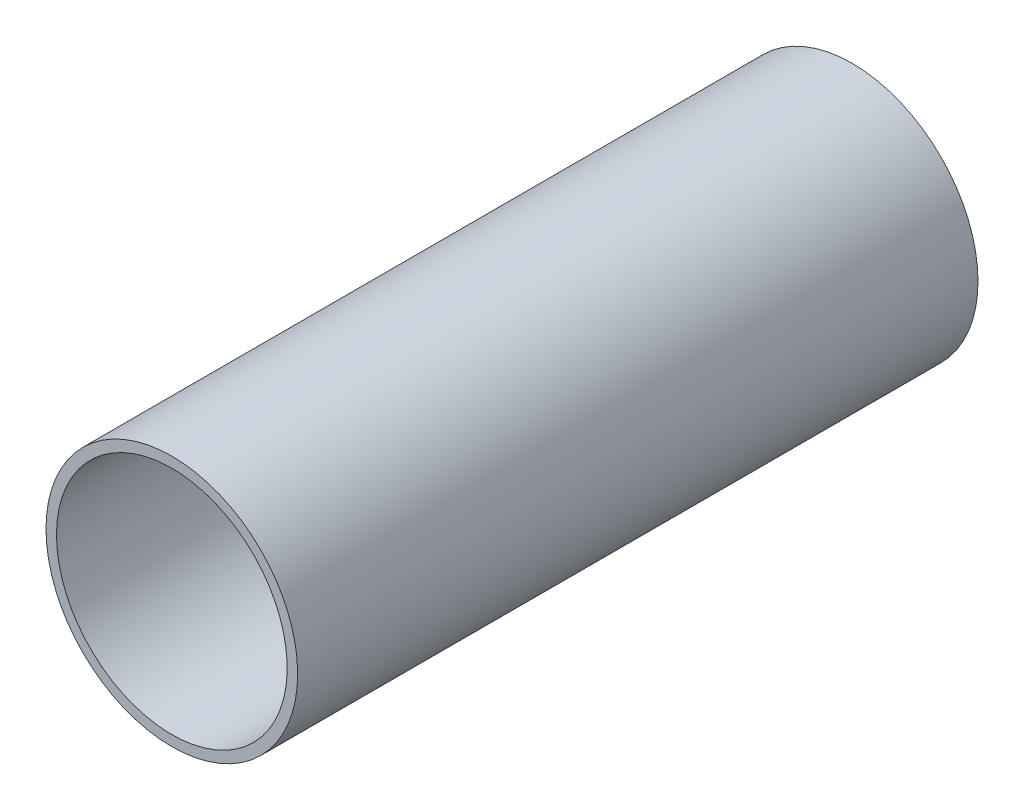
SolidWorks part; units mm, degrees
ref_plane "Front Plane" through (0, 0, 0) normal (0, 0, 1) x (1, 0, 0)
ref_plane "Top Plane" through (0, 0, 0) normal (0, 1, 0) x (1, 0, 0)
ref_plane "Right Plane" through (0, 0, 0) normal (1, 0, 0) x (0, 0, -1)
sketch "Sketch1" plane through (0, 0, 0) normal (0, 0, 1) x (1, 0, 0)
  circle A0 centre (0, 0) radius 76.2
  circle A1 centre (0, 0) radius 69.85
  dimension "D1" = 152.4
  dimension "D2" = 139.7
extrude "Boss-Extrude1" add sketch "Sketch1" along normal mid plane 412
